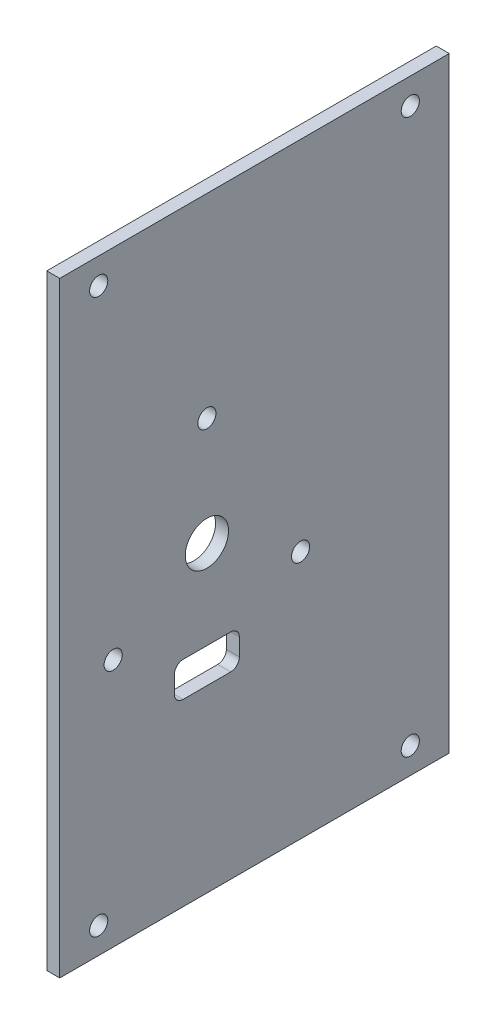
SolidWorks part; units mm, degrees
material "ABS"
ref_plane "Front Plane" through (0, 0, 0) normal (0, 0, 1) x (1, 0, 0)
ref_plane "Top Plane" through (0, 0, 0) normal (0, 1, 0) x (1, 0, 0)
ref_plane "Right Plane" through (0, 0, 0) normal (1, 0, 0) x (0, 0, -1)
sketch "Sketch1" plane through (0, 0, 0) normal (1, 0, 0) x (0, 0, -1)
  line L0 (34, -90.5) -> (28.5, -90.5)
  line L1 (0, 0) -> (90, 0)
  line L2 (0, 0) -> (0, -140)
  line L3 (0, -140) -> (90, -140)
  line L4 (90, 0) -> (90, -140)
  line L5 (26.5, -92.5) -> (26.5, -96.5)
  line L6 (34, -70) -> (34, -90.5) construction
  line L7 (28.5, -98.5) -> (39.5, -98.5)
  line L8 (41.5, -96.5) -> (41.5, -92.5)
  line L9 (39.5, -90.5) -> (34, -90.5)
  line L10 (45, 0) -> (45, -140) construction
  line L11 (0, -70) -> (90, -70) construction
  circle A0 centre (34, -70) radius 5
  circle A1 centre (34, -45) radius 2.1
  circle A2 centre (55.6506, -82.5) radius 2.1
  circle A3 centre (12.3494, -82.5) radius 2.1
  arc A4 (41.5, -96.5) -> (39.5, -98.5) centre (39.5, -96.5) cw
  arc A5 (39.5, -90.5) -> (41.5, -92.5) centre (39.5, -92.5) cw
  arc A6 (28.5, -98.5) -> (26.5, -96.5) centre (28.5, -96.5) cw
  arc A7 (26.5, -92.5) -> (28.5, -90.5) centre (28.5, -92.5) cw
  circle A8 centre (9, -6) radius 2.1
  circle A9 centre (81, -6) radius 2.1
  circle A10 centre (81, -134) radius 2.1
  circle A11 centre (9, -134) radius 2.1
  point P21 (41.5, -98.5)
  point P26 (26.5, -98.5)
  point P29 (26.5, -90.5)
  dimension "D5" = 10
  dimension "D7" = 4.2
  dimension "D13" = 2
  dimension "D17" = 4.2
  dimension "D3" = 70
  dimension "D4" = 34
  dimension "D6" = 25
  dimension "D9" = 20.5
  dimension "D10" = 7.5
  dimension "D11" = 15
  dimension "D12" = 8
  dimension "D14" = 90
  dimension "D2" = 140
  dimension "D15" = 9
  dimension "D16" = 6
  dimension "D8" = 3
extrude "Boss-Extrude1" add sketch "Sketch1" along normal blind 3
equation "\"Depth\"= 90mm"
equation "\"Height\"= 140mm"
equation "\"Width\"= 64mm"
equation "\"D14@Sketch1\"=\"Depth\""
equation "\"D2@Sketch1\"=\"Height\""
